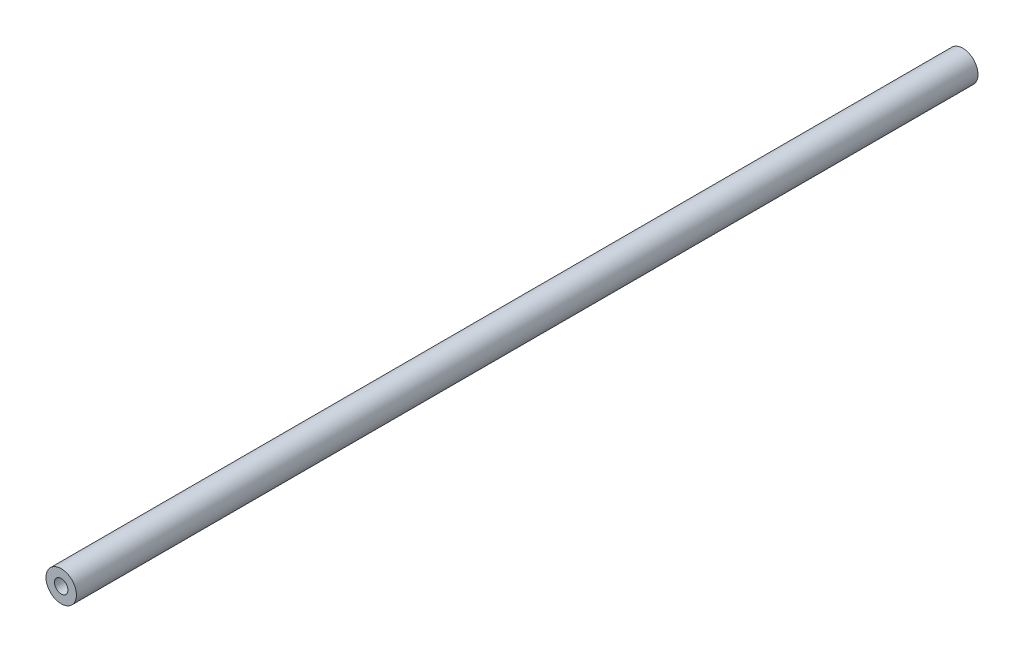
SolidWorks part; units mm, degrees
ref_plane "Front Plane" through (0, 0, 0) normal (0, 0, 1) x (1, 0, 0)
ref_plane "Top Plane" through (0, 0, 0) normal (0, 1, 0) x (1, 0, 0)
ref_plane "Right Plane" through (0, 0, 0) normal (1, 0, 0) x (0, 0, -1)
sketch "Sketch1" plane through (0, 0, 0) normal (0, 0, 1) x (1, 0, 0)
  circle A0 centre (0, 0) radius 3.9688
  dimension "D1" = 7.9375
extrude "Boss-Extrude1" add sketch "Sketch1" along normal mid plane 234.95
hole_wizard "#6-32 Tapped Hole1" positions "Sketch3" profile "Sketch2" tap size "#6-32" standard "ANSI Inch"
sketch "Sketch3" plane through (0, 0, -117.475) normal (0, 0, -1) x (-1, 0, 0)
  point P0 (0, 0)
sketch "Sketch2" plane through (0, 0, -117.475) normal (1, 0, 0) x (0, 1, 0)
  line L0 (0, 0) -> (0, 10.2107)
  line L1 (0, 10.2107) -> (1.3525, 9.398)
  line L2 (1.3525, 9.398) -> (1.3525, 7.112)
  line L3 (1.3525, 7.112) -> (1.7526, 7.112)
  line L4 (1.7526, 7.112) -> (1.7526, 0)
  line L5 (1.7526, 0) -> (0, 0)
  line L10 (0, 10.2107) -> (-1.3526, 9.398) construction
  line L11 (0, -6.35) -> (0, 107.95) construction
  dimension "Tap Drill Dia." = 2.7051
  dimension "Tap Drill Depth" = 9.398
  dimension "Thread Major Dia." = 3.5052
  dimension "Thread Depth" = 7.112
  dimension "Drill Angle" = 118
hole_wizard "#6-32 Tapped Hole2" positions "Sketch5" profile "Sketch4" tap size "#6-32" standard "ANSI Inch"
sketch "Sketch5" plane through (0, 0, 117.475) normal (0, 0, 1) x (1, 0, 0)
  point P0 (0, 0)
sketch "Sketch4" plane through (0, 0, 117.475) normal (1, 0, 0) x (0, -1, 0)
  line L0 (0, 0) -> (0, 10.2107)
  line L1 (0, 10.2107) -> (1.3525, 9.398)
  line L2 (1.3525, 9.398) -> (1.3525, 7.112)
  line L3 (1.3525, 7.112) -> (1.7526, 7.112)
  line L4 (1.7526, 7.112) -> (1.7526, 0)
  line L5 (1.7526, 0) -> (0, 0)
  line L10 (0, 10.2107) -> (-1.3526, 9.398) construction
  line L11 (0, -6.35) -> (0, 107.95) construction
  dimension "Tap Drill Dia." = 2.7051
  dimension "Tap Drill Depth" = 9.398
  dimension "Thread Major Dia." = 3.5052
  dimension "Thread Depth" = 7.112
  dimension "Drill Angle" = 118
